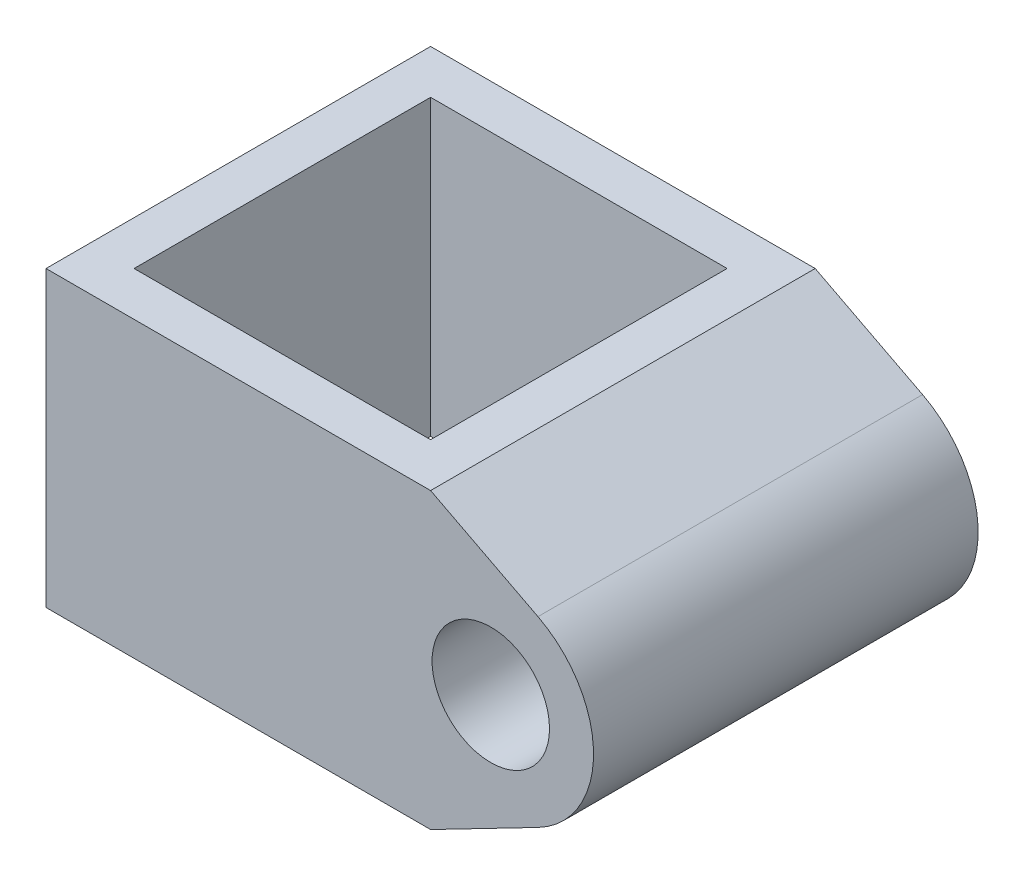
SolidWorks part; units mm, degrees
ref_plane "Front Plane" through (0, 0, 0) normal (0, 0, 1) x (1, 0, 0)
ref_plane "Top Plane" through (0, 0, 0) normal (0, 1, 0) x (1, 0, 0)
ref_plane "Right Plane" through (0, 0, 0) normal (1, 0, 0) x (0, 0, -1)
sketch "Sketch1" plane through (0, 0, 0) normal (0, 1, 0) x (1, 0, 0)
  line L0 (-3, 23.2) -> (23.2, 23.2)
  line L1 (0, 0) -> (20.2, 0)
  line L2 (0, 0) -> (0, 20.2)
  line L3 (0, 20.2) -> (20.2, 20.2)
  line L4 (20.2, 0) -> (20.2, 20.2)
  line L5 (23.2, -3) -> (23.2, 23.2)
  line L6 (-3, -3) -> (23.2, -3)
  line L7 (-3, -3) -> (-3, 23.2)
  dimension "D1" = 20.2
  dimension "D2" = 3
extrude "Boss-Extrude1" add sketch "Sketch1" along normal blind 20
sketch "Sketch2" plane through (0, 0, 3) normal (0, 0, 1) x (1, 0, 0)
  line L0 (-3, 10) -> (23.2, 10) construction
  line L1 (-3, 20) -> (-3, 0) construction
  line L2 (23.2, 20) -> (23.2, 0) construction
  line L3 (23.2, 20) -> (30.5149, 16.2181)
  line L4 (23.2, 0) -> (30.5149, 3.7819)
  circle A0 centre (27.3, 10) radius 4
  circle A1 centre (27.3, 10) radius 7
  point P16 (27.4066, 10)
  point P17 (27.8595, 10)
  line M3 (23.2, 0) -> (23.2, 20)
  dimension "D1" = 8
  dimension "D3" = 4.1
  dimension "D2" = 3
extrude "Boss-Extrude4" add sketch "Sketch2" against normal up to surface (26.2 mm away) contours A1 A0 M3 | A1 L3 M3 | A1 L4 M3 up to face at (10.1, 10, -23.2)
